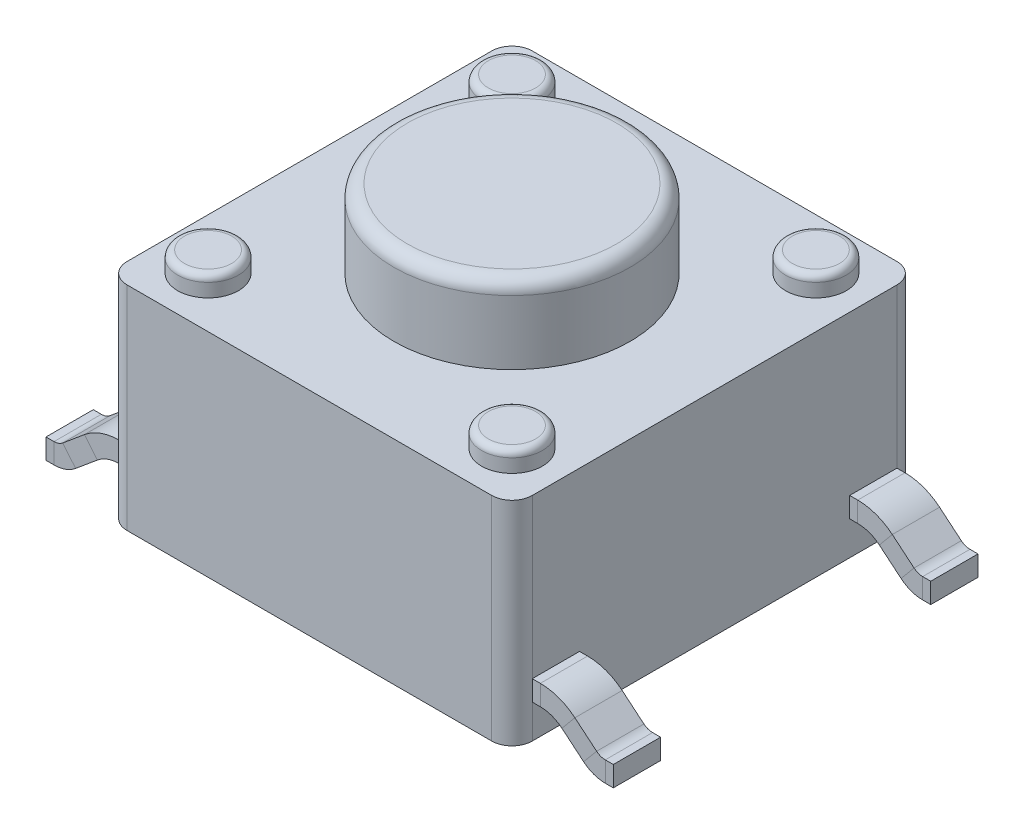
SolidWorks part; units mm, degrees
ref_plane "Front" through (0, 0, 0) normal (0, 0, 1) x (1, 0, 0)
ref_plane "Top" through (0, 0, 0) normal (0, 1, 0) x (1, 0, 0)
ref_plane "Right" through (0, 0, 0) normal (1, 0, 0) x (0, 0, -1)
sketch "Sketch1" plane through (0, 0, 0) normal (0, 1, 0) x (1, 0, 0)
  line L1 (-2.7, 3) -> (2.7, 3)
  line L2 (-3, 2.7) -> (-3, -2.7)
  line L3 (-2.7, -3) -> (2.7, -3)
  line L4 (3, 2.7) -> (3, -2.7)
  line L5 (-3, 3) -> (3, -3) construction
  line L6 (-3, -3) -> (3, 3) construction
  arc A0 (-3, -2.7) -> (-2.7, -3) centre (-2.7, -2.7) ccw
  arc A1 (-2.7, 3) -> (-3, 2.7) centre (-2.7, 2.7) ccw
  arc A2 (2.7, 3) -> (3, 2.7) centre (2.7, 2.7) cw
  arc A3 (2.7, -3) -> (3, -2.7) centre (2.7, -2.7) ccw
  point P0 (0, 0)
  dimension "D3" = 0.3
  dimension "D1" = 6
  dimension "D2" = 6
extrude "Boss-Extrude1" add sketch "Sketch1" along normal blind 3.15
sketch "Sketch2" plane through (0, 3.15, 0) normal (0, 1, 0) x (1, 0, 0)
  circle A0 centre (0, 0) radius 1.75
  dimension "D1" = 3.5
extrude "Boss-Extrude2" add sketch "Sketch2" along normal blind 1.15
fillet "Fillet1" radius 0.2 1 edges at (0, 4.3, 1.75)
sketch "Sketch3" plane through (0, 3.15, 0) normal (0, 1, 0) x (1, 0, 0)
  line L1 (-2.25, -2.25) -> (2.25, -2.25) construction
  line L2 (-2.25, -2.25) -> (-2.25, 2.25) construction
  line L3 (-2.25, 2.25) -> (2.25, 2.25) construction
  line L4 (2.25, -2.25) -> (2.25, 2.25) construction
  line L5 (-2.25, -2.25) -> (2.25, 2.25) construction
  line L6 (-2.25, 2.25) -> (2.25, -2.25) construction
  circle A0 centre (-2.25, 2.25) radius 0.45
  circle A1 centre (2.25, 2.25) radius 0.45
  circle A2 centre (2.25, -2.25) radius 0.45
  circle A3 centre (-2.25, -2.25) radius 0.45
  point P0 (0, 0)
  dimension "D2" = 0.9
  dimension "D1" = 4.5
extrude "Boss-Extrude3" add sketch "Sketch3" along normal blind 0.3
sketch "Sketch4" plane through (3, 0, 0) normal (1, 0, 0) x (0, 0, -1)
  line L0 (-2.7, 3.15) -> (-2.7, 0) construction
  line L1 (-2.7, 0.8) -> (-2, 0.8)
  line L2 (-2.7, 0.8) -> (-2.7, 0.5)
  line L3 (-2.7, 0.5) -> (-2, 0.5)
  line L4 (-2, 0.8) -> (-2, 0.5)
  dimension "D1" = 0.7
  dimension "D2" = 0.3
  dimension "D3" = 0.5
ref_plane "Plane1" through (0, 0, 2.7) normal (0, 0, 1) x (1, 0, 0)
sketch "Sketch5" plane through (0, 0, 2.7) normal (0, 0, 1) x (1, 0, 0)
  line L0 (3, 0.5) -> (3.119, 0.5)
  line L1 (3.4391, 0.3841) -> (3.7609, 0.1159)
  line L2 (4.081, 0) -> (4.2, 0)
  arc A0 (3.7609, 0.1159) -> (4.081, 0) centre (4.081, 0.5) ccw
  arc A1 (3.119, 0.5) -> (3.4391, 0.3841) centre (3.119, 0) cw
  point P8 (3.9, 0)
  point P11 (3.3, 0.5)
  dimension "D5" = 0.5
  dimension "D1" = 4.2
  dimension "D3" = 0.3
  dimension "D4" = 0.3
sweep "Sweep1" add profiles "Sketch4" path "Sketch5"
mirror "Mirror1" about plane through (0, 0, 0) normal (0, 0, 1) of "Sweep1"
mirror "Mirror2" about plane through (0, 0, 0) normal (1, 0, 0) of "Mirror1", "Sweep1"
fillet "Fillet2" radius 0.1 4 edges at (-2.25, 3.45, -1.8) (2.25, 3.45, -1.8) (2.25, 3.45, 2.7) (-2.25, 3.45, 2.7)
